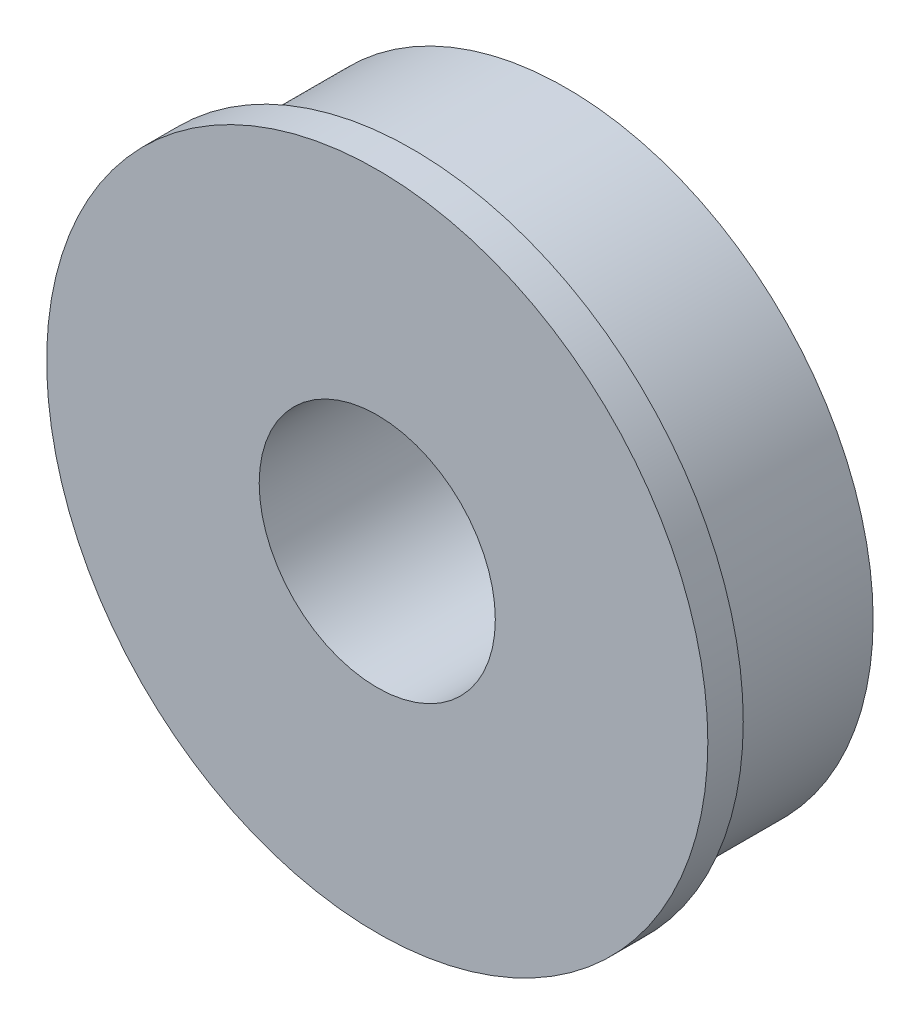
SolidWorks part; units mm, degrees
ref_plane "前视基准面" through (0, 0, 0) normal (0, 0, 1) x (1, 0, 0)
ref_plane "上视基准面" through (0, 0, 0) normal (0, 1, 0) x (1, 0, 0)
ref_plane "右视基准面" through (0, 0, 0) normal (1, 0, 0) x (0, 0, -1)
sketch "草图2" plane through (0, 0, 0) normal (0, 0, 1) x (1, 0, 0)
  circle A0 centre (0, 0) radius 5
  circle A1 centre (0, 0) radius 13
  dimension "D1" = 10
  dimension "D2" = 26
extrude "凸台-拉伸1" add sketch "草图2" along normal blind 8
sketch "草图3" plane through (0, 0, 8) normal (0, 0, 1) x (1, 0, 0)
  circle A0 centre (0, 0) radius 14
  circle A1 centre (0, 0) radius 5
  circle A2 centre (0, 0) radius 5 construction
  dimension "D1" = 28
extrude "凸台-拉伸2" add sketch "草图3" against normal blind 1.5
